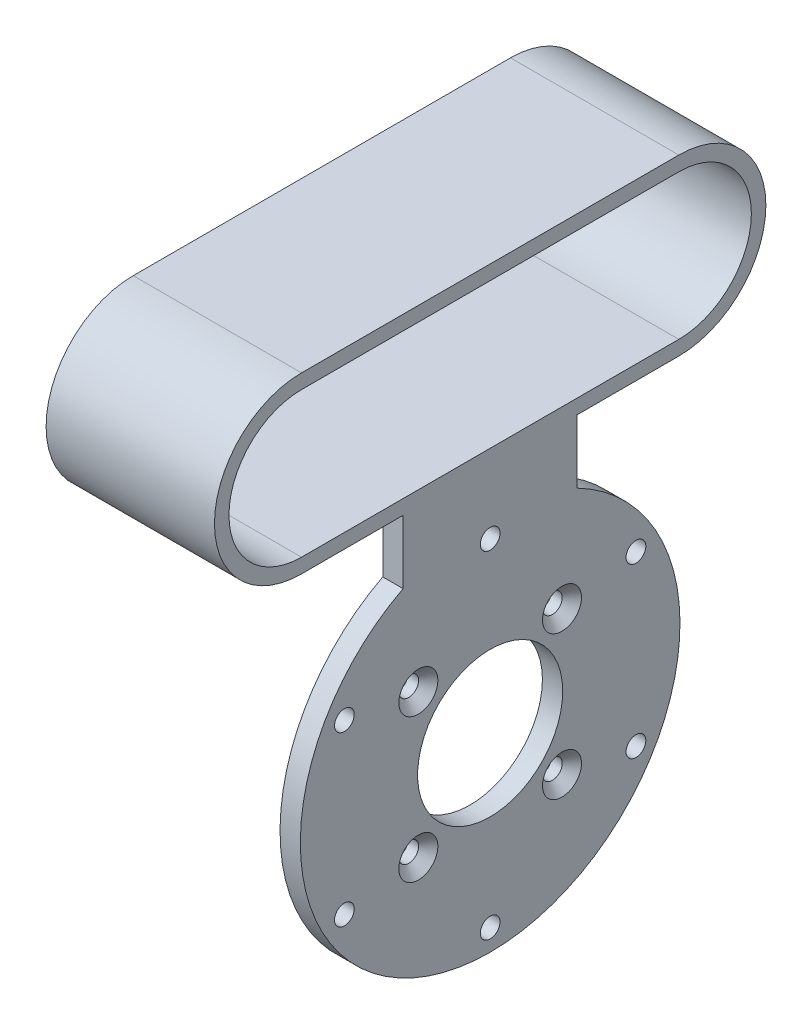
SolidWorks part; units mm, degrees
material "6063-T5"
ref_plane "Front" through (0, 0, 0) normal (0, 0, 1) x (1, 0, 0)
ref_plane "Top" through (0, 0, 0) normal (0, 1, 0) x (1, 0, 0)
ref_plane "Right" through (0, 0, 0) normal (1, 0, 0) x (0, 0, -1)
sketch "Croquis1" plane through (0, 0, 0) normal (1, 0, 0) x (0, 0, -1)
  line L0 (-32.5, 55) -> (32.5, 55) construction
  line L1 (-32.5, 70) -> (32.5, 70) construction
  line L2 (-32.5, 40) -> (32.5, 40) construction
  line L3 (0, 50) -> (0, -50) construction
  line L4 (-15, 40) -> (-15, 29.0567)
  line L5 (15, 40) -> (15, 29.0567)
  line L6 (-32.5, 55) -> (32.5, 55) construction
  line L7 (-32.5, 70) -> (32.5, 70)
  line L9 (-32.5, 40) -> (-15, 40)
  line L10 (32.5, 40) -> (15, 40)
  line L11 (-32.5, 55) -> (32.5, 55) construction
  line L12 (-32.5, 67.5) -> (32.5, 67.5)
  line L13 (-32.5, 42.5) -> (32.5, 42.5)
  arc A0 (-15, 29.0567) -> (15, 29.0567) centre (0, 0) ccw
  circle A1 centre (0, 0) radius 12.5
  arc A2 (-32.5, 70) -> (-32.5, 40) centre (-32.5, 55) ccw construction
  arc A3 (32.5, 40) -> (32.5, 70) centre (32.5, 55) ccw construction
  arc A4 (-32.5, 70) -> (-32.5, 40) centre (-32.5, 55) ccw
  arc A5 (32.5, 40) -> (32.5, 70) centre (32.5, 55) ccw
  arc A6 (-32.5, 67.5) -> (-32.5, 42.5) centre (-32.5, 55) ccw
  arc A7 (32.5, 42.5) -> (32.5, 67.5) centre (32.5, 55) ccw
  point P1 (0, 55)
  point P6 (0, 55)
  point P19 (0, 55)
  dimension "D1" = 65.4
  dimension "D2" = 25
  dimension "D3" = 15
  dimension "D7" = 12.5
  dimension "D4" = 55
  dimension "D5" = 65
  dimension "D6" = 15
extrude "Saliente-Extruir1" add sketch "Croquis1" along normal blind 3.5
hole_wizard "Taladro de margen para M31" positions "Croquis2" profile "Croquis4" hole size "M3" standard "Ansi Metric" end condition up to next
sketch "Croquis2" plane through (3.5, 0, 0) normal (1, 0, 0) x (0, 0, -1)
  line L0 (0, 50) -> (0, -50) construction
  line L1 (50, 0) -> (-50, 0) construction
  point P0 (0, 29)
  point P11 (25.1147, 14.5)
  point P12 (25.1147, -14.5)
  point P13 (0, -29)
  point P14 (-25.1147, -14.5)
  point P15 (-25.1147, 14.5)
  dimension "D1" = 29
  dimension "D3" = 29
  dimension "D2" = 6
sketch "Croquis4" plane through (3.5, 29, 0) normal (0, 1, 0) x (0, 0, -1)
  line L0 (0, 0) -> (0, 3.5)
  line L1 (0, 3.5) -> (1.7, 3.5)
  line L2 (1.7, 3.5) -> (1.7, 0)
  line L5 (1.7, 0) -> (0, 0)
  line L11 (0, -6.35) -> (0, 107.95) construction
  dimension "Diámetro de taladro hasta el siguiente" = 3.4
  dimension "Profundidad de taladro hasta el siguiente" = 3.5
hole_wizard "Refrentado para tornillo tapón con cabeza plana de clavija de M31" positions "Croquis5" profile "Croquis7" countersink size "M3" standard "Ansi Metric" end condition up to next
sketch "Croquis5" plane through (3.5, 0, 0) normal (1, 0, 0) x (0, 0, -1)
  line L1 (-12.3744, -12.3744) -> (12.3744, -12.3744) construction
  line L2 (-12.3744, -12.3744) -> (-12.3744, 12.3744) construction
  line L3 (-12.3744, 12.3744) -> (12.3744, 12.3744) construction
  line L4 (12.3744, -12.3744) -> (12.3744, 12.3744) construction
  line L5 (-12.3744, -12.3744) -> (12.3744, 12.3744) construction
  line L6 (-12.3744, 12.3744) -> (12.3744, -12.3744) construction
  point P2 (12.3744, 12.3744)
  point P29 (-12.3744, -12.3744)
  point P30 (-12.3744, 12.3744)
  point P31 (12.3744, -12.3744)
  dimension "D1" = 35
sketch "Croquis7" plane through (3.5, 12.3744, -12.3744) normal (0, 1, 0) x (0, 0, -1)
  line L0 (0, 0) -> (0, 3.5)
  line L1 (0, 3.5) -> (1.7, 3.5)
  line L2 (1.7, 3.5) -> (1.7, 1.66)
  line L3 (1.7, 1.66) -> (3.36, 0)
  line L5 (3.36, 0) -> (0, 0)
  line L6 (-1.7, 1.66) -> (-3.36, 0) construction
  line L11 (0, -6.35) -> (0, 107.95) construction
  dimension "Diámetro de taladro hasta el siguiente" = 3.4
  dimension "Profundidad de taladro hasta el siguiente" = 3.5
  dimension "Diámetro de avellanado cercano" = 6.72
  dimension "Ángulo de avellanado cercano" = 90
sketch "Croquis8" plane through (3.5, 0, 0) normal (1, 0, 0) x (0, 0, -1)
  line L0 (15, 40) -> (32.5, 40) construction
  line L1 (32.5, 70) -> (-32.5, 70) construction
  line L2 (-32.5, 40) -> (-15, 40) construction
  line L3 (15, 40) -> (32.5, 40)
  line L4 (32.5, 70) -> (-32.5, 70)
  line L5 (-32.5, 40) -> (-15, 40)
  line L6 (15, 40) -> (-15, 40)
  line L7 (-32.5, 55) -> (32.5, 55) construction
  line L8 (-32.5, 67.5) -> (32.5, 67.5)
  line L9 (-32.5, 42.5) -> (32.5, 42.5)
  arc A0 (32.5, 40) -> (32.5, 70) centre (32.5, 55) ccw construction
  arc A1 (-32.5, 70) -> (-32.5, 40) centre (-32.5, 55) ccw construction
  arc A2 (32.5, 40) -> (32.5, 70) centre (32.5, 55) ccw
  arc A3 (-32.5, 70) -> (-32.5, 40) centre (-32.5, 55) ccw
  arc A4 (-32.5, 67.5) -> (-32.5, 42.5) centre (-32.5, 55) ccw
  arc A5 (32.5, 42.5) -> (32.5, 67.5) centre (32.5, 55) ccw
  point P3 (0, 55)
  dimension "D1" = 12.5
extrude "Saliente-Extruir2" add sketch "Croquis8" against normal blind 29
sketch "Croquis12" plane through (-25.5, 0, 0) normal (-1, 0, 0) x (0, 0, 1)
  line L0 (32.5, 42.5) -> (-32.5, 42.5) construction
  line L1 (-32.5, 67.5) -> (32.5, 67.5) construction
  line L2 (32.5, 42.5) -> (-32.5, 42.5)
  line L3 (-32.5, 67.5) -> (32.5, 67.5)
  arc A0 (32.5, 42.5) -> (32.5, 67.5) centre (32.5, 55) ccw construction
  arc A1 (-32.5, 67.5) -> (-32.5, 42.5) centre (-32.5, 55) ccw construction
  arc A2 (32.5, 42.5) -> (32.5, 67.5) centre (32.5, 55) ccw
  arc A3 (-32.5, 67.5) -> (-32.5, 42.5) centre (-32.5, 55) ccw
extrude "Saliente-Extruir3" add sketch "Croquis12" against normal blind 3.5
hole_wizard "Refrentado para tornillo con cabeza troncocónica de M31" positions "Croquis9" profile "Croquis11" counterbore size "M3" standard "Ansi Metric" end condition up to next
sketch "Croquis9" plane through (-25.5, 0, 0) normal (-1, 0, 0) x (0, 0, 1)
  line L0 (-22.5, 55) -> (22.5, 55) construction
  line L3 (0, -50) -> (0, 50) construction
  line L4 (-15, 40) -> (15, 40) construction
  point P0 (-22.5, 55)
  point P1 (22.5, 55)
  point P4 (0, 55)
  dimension "D1" = 45
  dimension "D2" = 15
sketch "Croquis11" plane through (-25.5, 55, -22.5) normal (0, 1, 0) x (0, 0, 1)
  line L0 (0, 0) -> (0, 3.5)
  line L1 (0, 3.5) -> (1.7, 3.5)
  line L3 (1.7, 3.5) -> (1.7, 2.4)
  line L4 (1.7, 2.4) -> (3.5, 2.4)
  line L5 (3.5, 2.4) -> (3.5, 0)
  line L7 (3.5, 0) -> (0, 0)
  line L11 (0, -6.35) -> (0, 107.95) construction
  dimension "Diámetro de taladro hasta el siguiente" = 3.4
  dimension "Profundidad de taladro hasta el siguiente" = 3.5
  dimension "Diámetro de refrentado" = 7
  dimension "Profundidad de refrentado" = 2.4
